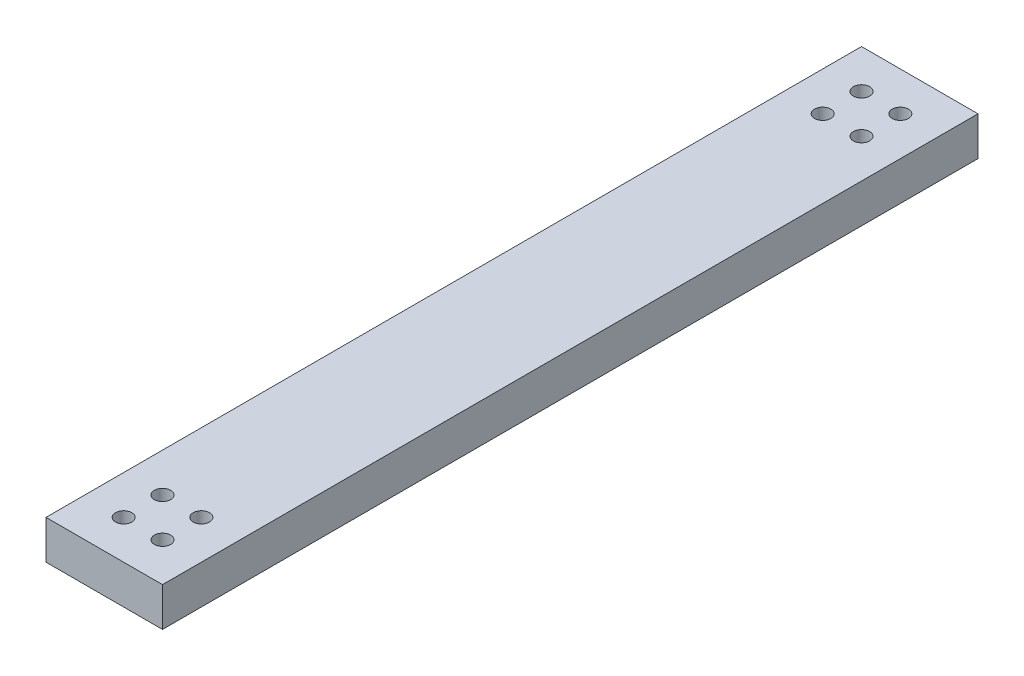
SolidWorks part; units mm, degrees
ref_plane "Спереди" through (0, 0, 0) normal (0, 0, 1) x (1, 0, 0)
ref_plane "Сверху" through (0, 0, 0) normal (0, 1, 0) x (1, 0, 0)
ref_plane "Справа" through (0, 0, 0) normal (1, 0, 0) x (0, 0, -1)
sketch "Эскиз1" plane through (0, 0, 0) normal (0, 1, 0) x (1, 0, 0)
  line L8 (-15, -195) -> (15, -195)
  line L12 (-15, 15) -> (-15, -195)
  line L13 (15, 15) -> (15, -195)
  line L14 (15, 15) -> (-15, 15)
  circle A0 centre (-5, 5) radius 2.1
  circle A1 centre (5, 5) radius 2.1
  circle A2 centre (-5, -5) radius 2.1
  circle A3 centre (5, -5) radius 2.1
  circle A4 centre (-5, -175) radius 2.1
  circle A5 centre (5, -175) radius 2.1
  circle A6 centre (5, -185) radius 2.1
  circle A7 centre (-5, -185) radius 2.1
extrude "Бобышка-Вытянуть2" add sketch "Эскиз1" along normal blind 10
